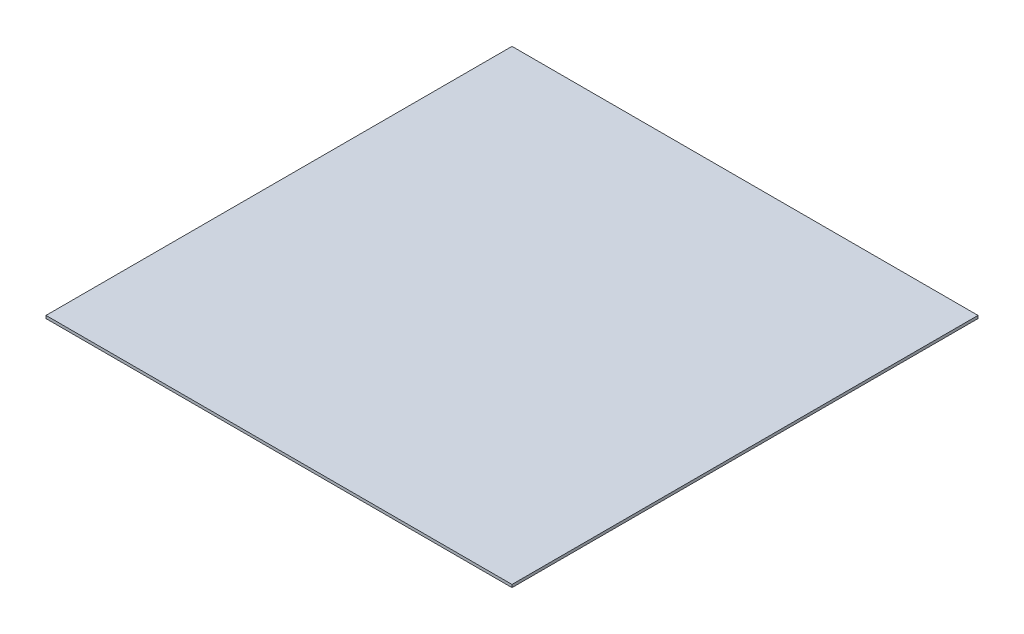
SolidWorks part; units mm, degrees
ref_plane "Спереди" through (0, 0, 0) normal (0, 0, 1) x (1, 0, 0)
ref_plane "Сверху" through (0, 0, 0) normal (0, 1, 0) x (1, 0, 0)
ref_plane "Справа" through (0, 0, 0) normal (1, 0, 0) x (0, 0, -1)
other "Configuration Table"
sketch "Эскиз1" plane through (0, 0, 0) normal (0, 1, 0) x (1, 0, 0)
  line L1 (-250, 250) -> (250, 250)
  line L2 (-250, 250) -> (-250, -250)
  line L3 (-250, -250) -> (250, -250)
  line L4 (250, 250) -> (250, -250)
  line L5 (-250, 250) -> (250, -250) construction
  line L6 (-250, -250) -> (250, 250) construction
  point P0 (0, 0)
  dimension "D1" = 500
extrude "Бобышка-Вытянуть1" add sketch "Эскиз1" along normal mid plane 3
sketch "Эскиз2" plane through (0, 0, 0) normal (0, 1, 0) x (1, 0, 0)
  line L0 (-250, 0) -> (250, 0) construction
  line L1 (-250, 250) -> (-250, -250) construction
  line L2 (250, -250) -> (250, 250) construction
